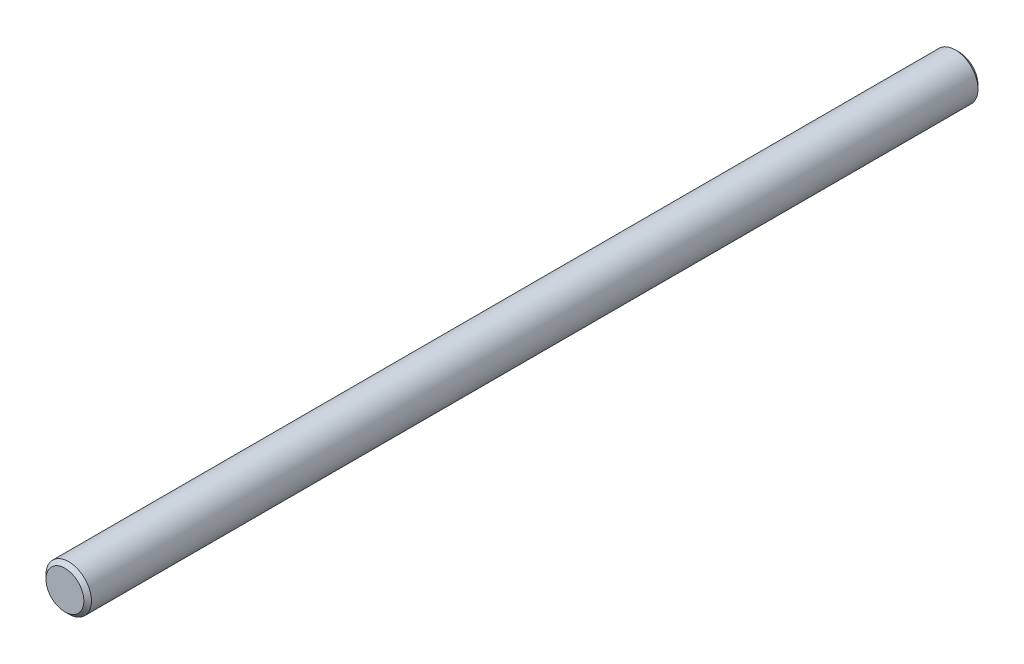
SolidWorks part; units mm, degrees
ref_plane "Front" through (0, 0, 0) normal (0, 0, 1) x (1, 0, 0)
ref_plane "Top" through (0, 0, 0) normal (0, 1, 0) x (1, 0, 0)
ref_plane "Right" through (0, 0, 0) normal (1, 0, 0) x (0, 0, -1)
sketch "Sketch1" plane through (0, 0, 0) normal (0, 0, 1) x (1, 0, 0)
  circle A0 centre (0, 0) radius 3
  dimension "D1" = 6
extrude "Boss-Extrude1" add sketch "Sketch1" along normal blind 118
chamfer "Chamfer1" distance 0.5 angle 45 2 edges at (3, 0, 0) (3, 0, 118)
